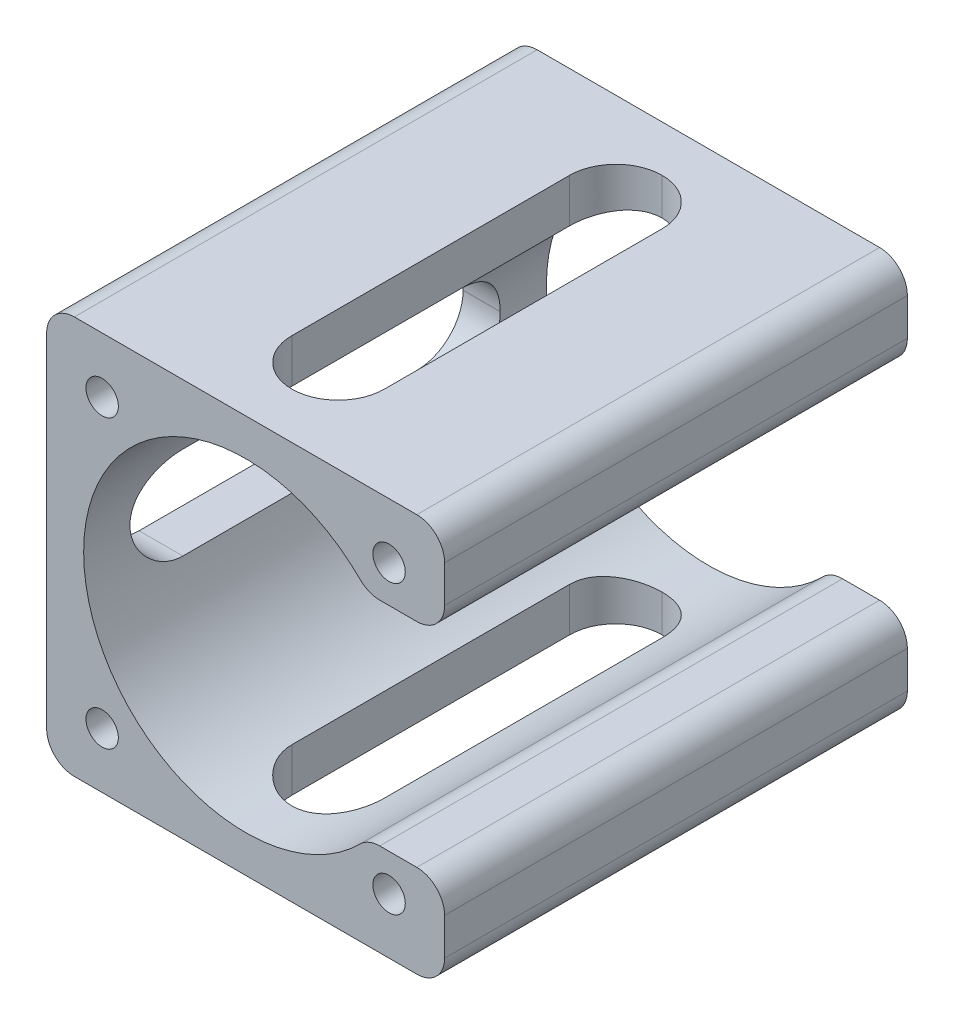
SolidWorks part; units mm, degrees
material "ABS"
ref_plane "Front Plane" through (0, 0, 0) normal (0, 0, 1) x (1, 0, 0)
ref_plane "Top Plane" through (0, 0, 0) normal (0, 1, 0) x (1, 0, 0)
ref_plane "Right Plane" through (0, 0, 0) normal (1, 0, 0) x (0, 0, -1)
sketch "Sketch1" plane through (0, 0, 0) normal (0, 0, 1) x (1, 0, 0)
  line L0 (-15.5, 15.5) -> (15.5, 15.5) construction
  line L1 (18.5, -21.5) -> (-18.5, -21.5)
  line L2 (21.5, -18.5) -> (21.5, -14.5)
  line L3 (18.5, 21.5) -> (-18.5, 21.5)
  line L4 (-21.5, -18.5) -> (-21.5, 18.5)
  line L5 (21.5, -21.5) -> (-21.5, 21.5) construction
  line L6 (21.5, 21.5) -> (-21.5, -21.5) construction
  line L7 (-15.5, 15.5) -> (-15.5, -15.5) construction
  line L8 (15.5, 15.5) -> (15.5, -15.5) construction
  line L9 (14.4914, 11.5) -> (18.5, 11.5)
  line L10 (14.4914, -11.5) -> (18.5, -11.5)
  line L11 (21.5, 14.5) -> (21.5, 18.5)
  arc A0 (12.3707, 12.378) -> (12.3707, -12.378) centre (0, 0) ccw
  circle A1 centre (-15.5, 15.5) radius 1.75
  circle A2 centre (-15.5, -15.5) radius 1.75
  circle A3 centre (15.5, -15.5) radius 1.75
  circle A4 centre (15.5, 15.5) radius 1.75
  arc A5 (18.5, -11.5) -> (21.5, -14.5) centre (18.5, -14.5) cw
  arc A6 (14.4914, -11.5) -> (12.3707, -12.378) centre (14.4914, -14.5) ccw
  arc A7 (14.4914, 11.5) -> (12.3707, 12.378) centre (14.4914, 14.5) cw
  arc A8 (21.5, 14.5) -> (18.5, 11.5) centre (18.5, 14.5) cw
  arc A9 (21.5, 18.5) -> (18.5, 21.5) centre (18.5, 18.5) ccw
  arc A10 (18.5, -21.5) -> (21.5, -18.5) centre (18.5, -18.5) ccw
  arc A11 (-18.5, -21.5) -> (-21.5, -18.5) centre (-18.5, -18.5) cw
  arc A12 (-18.5, 21.5) -> (-21.5, 18.5) centre (-18.5, 18.5) ccw
  dimension "D1" = 35
  dimension "D4" = 3.5
  dimension "D5" = 3.5
  dimension "D6" = 3.5
  dimension "D7" = 3.5
  dimension "D11" = 3
  dimension "D2" = 43
  dimension "D3" = 43
  dimension "D8" = 31
  dimension "D9" = 23
  dimension "D10" = 11.5
extrude "Boss-Extrude1" add sketch "Sketch1" along normal blind 50
sketch "Sketch2" plane through (0, 21.5, 0) normal (0, 1, 0) x (1, 0, 0)
  line L0 (0, 0) -> (0, -25) construction
  line L1 (-0.01, -45) -> (0.01, -45)
  line L2 (-5, -40.01) -> (-5, -9.99)
  line L3 (-0.01, -5) -> (0.01, -5)
  line L4 (5, -40.01) -> (5, -9.99)
  line L5 (-5, -45) -> (5, -5) construction
  line L6 (-5, -5) -> (5, -45) construction
  arc A0 (0.01, -45) -> (5, -40.01) centre (0.01, -40.01) ccw
  arc A1 (-0.01, -45) -> (-5, -40.01) centre (-0.01, -40.01) cw
  arc A2 (0.01, -5) -> (5, -9.99) centre (0.01, -9.99) cw
  arc A3 (-5, -9.99) -> (-0.01, -5) centre (-0.01, -9.99) cw
  point P0 (0, -25)
  dimension "D4" = 4.99
  dimension "D1" = 25
  dimension "D2" = 40
  dimension "D3" = 10
extrude "Cut-Extrude1" cut sketch "Sketch2" against normal blind 50
sketch "Sketch3" plane through (-21.5, 0, 0) normal (-1, 0, 0) x (0, 0, 1)
  line L0 (0, 0) -> (25, 0) construction
  line L1 (9.99, -5) -> (40.01, -5)
  line L2 (5, -0.01) -> (5, 0.01)
  line L3 (9.99, 5) -> (40.01, 5)
  line L4 (45, -0.01) -> (45, 0.01)
  line L5 (5, -5) -> (45, 5) construction
  line L6 (5, 5) -> (45, -5) construction
  arc A0 (40.01, 5) -> (45, 0.01) centre (40.01, 0.01) cw
  arc A1 (40.01, -5) -> (45, -0.01) centre (40.01, -0.01) ccw
  arc A2 (9.99, -5) -> (5, -0.01) centre (9.99, -0.01) cw
  arc A3 (5, 0.01) -> (9.99, 5) centre (9.99, 0.01) cw
  point P0 (25, 0)
  dimension "D4" = 4.99
  dimension "D1" = 25
  dimension "D2" = 40
  dimension "D3" = 10
extrude "Cut-Extrude2" cut sketch "Sketch3" against normal blind 50
